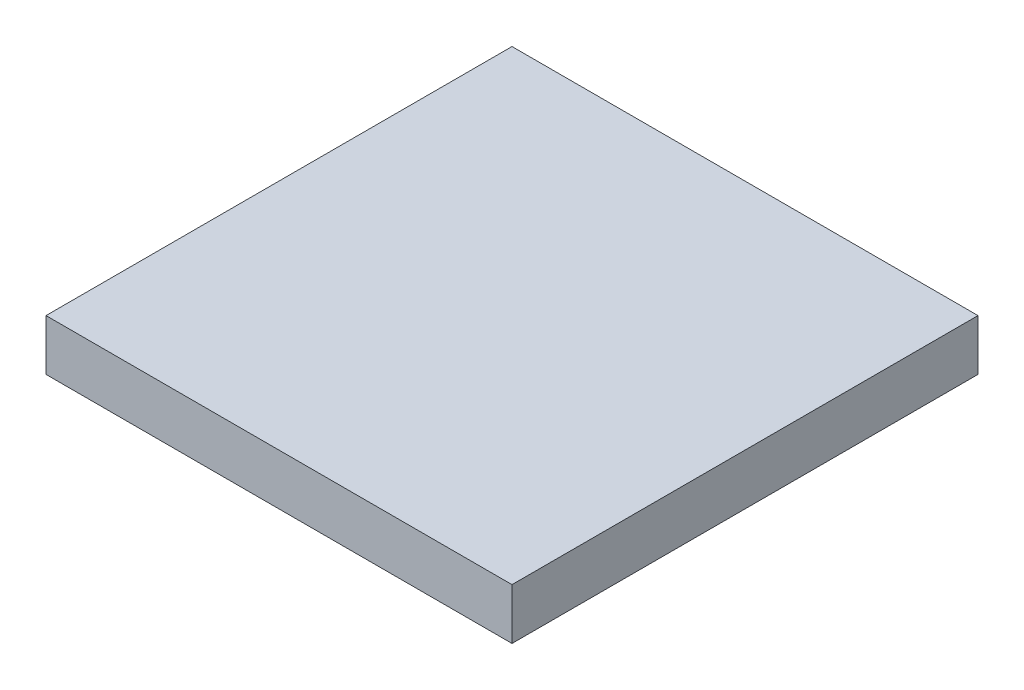
SolidWorks part; units mm, degrees
ref_plane "Front Plane" through (0, 0, 0) normal (0, 0, 1) x (1, 0, 0)
ref_plane "Top Plane" through (0, 0, 0) normal (0, 1, 0) x (1, 0, 0)
ref_plane "Right Plane" through (0, 0, 0) normal (1, 0, 0) x (0, 0, -1)
sketch "Sketch1" plane through (0, 0, 0) normal (0, 0, 1) x (1, 0, 0)
  line L7 (-50.8, -5.5562) -> (50.8, -5.5562)
  line L8 (-50.8, -5.5562) -> (-50.8, 5.5562)
  line L9 (-50.8, 5.5562) -> (50.8, 5.5562)
  line L10 (50.8, -5.5562) -> (50.8, 5.5562)
  line L11 (-50.8, -5.5562) -> (50.8, 5.5562) construction
  line L12 (-50.8, 5.5562) -> (50.8, -5.5562) construction
  point P4 (0, 0)
  point P14 (0, 0)
  dimension "Width" = 101.6
  dimension "Thickness" = 11.1125
sketch "Sketch2" plane through (0, 0, 0) normal (0, 1, 0) x (0, 0, -1)
  line L0 (50.8, 50.8) -> (-50.8, 50.8) construction
  point P0 (76.2, 50.8)
  point P4 (0, 50.8)
  point P6 (-76.2, 50.8)
  dimension "Length" = 101.6
  dimension "D1" = 127
  dimension "D2" = 127
sketch "Sketch3" plane through (0, 0, 0) normal (0, 0, 1) x (1, 0, 0)
  line L6 (-50.8, 5.5562) -> (50.8, 5.5562)
  line L7 (50.8, 5.5562) -> (50.8, -5.5562)
  line L8 (50.8, -5.5562) -> (-50.8, -5.5562)
  line L9 (-50.8, -5.5562) -> (-50.8, 5.5562)
extrude "Boss-Extrude1" add sketch "Sketch3" along normal mid plane 101.6
equation "\"D1@Boss-Extrude1\" = \"Length@Sketch2\""
equation "\"D1@Sketch2\"=\"Width@Sketch1\" * 1.25"
equation "\"D2@Sketch2\"=\"D1@Sketch2\""
